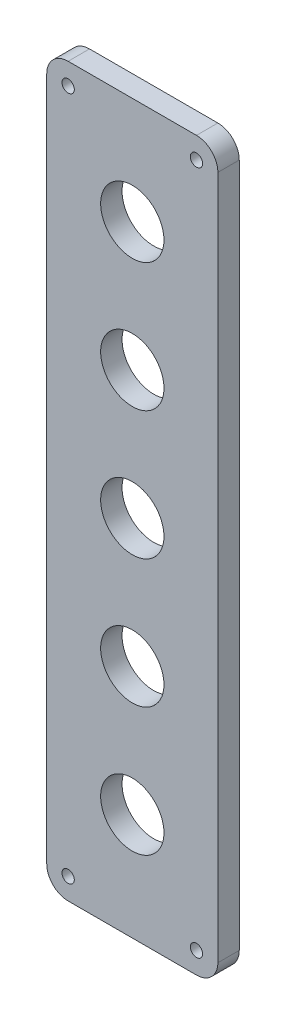
SolidWorks part; units mm, degrees
ref_plane "Front Plane" through (0, 0, 0) normal (0, 0, 1) x (1, 0, 0)
ref_plane "Top Plane" through (0, 0, 0) normal (0, 1, 0) x (1, 0, 0)
ref_plane "Right Plane" through (0, 0, 0) normal (1, 0, 0) x (0, 0, -1)
sketch "Sketch1" plane through (0, 0, 0) normal (0, 0, 1) x (1, 0, 0)
  line L1 (-25.4, -107.95) -> (25.4, -107.95)
  line L2 (-25.4, -107.95) -> (-25.4, 107.95)
  line L3 (-25.4, 107.95) -> (25.4, 107.95)
  line L4 (25.4, -107.95) -> (25.4, 107.95)
  line L5 (-25.4, -107.95) -> (25.4, 107.95) construction
  line L6 (-25.4, 107.95) -> (25.4, -107.95) construction
  point P0 (0, 0)
  dimension "D1" = 50.8
  dimension "D2" = 215.9
extrude "Boss-Extrude1" add sketch "Sketch1" along normal blind 6.35
sketch "Sketch2" plane through (0, 0, 6.35) normal (0, 0, 1) x (1, 0, 0)
  circle A0 centre (0, 0) radius 9.398
  dimension "D1" = 18.796
extrude "Cut-Extrude1" cut sketch "Sketch2" against normal blind 6.35
pattern_linear "LPattern1" count 3 spacing 38.1 along (0, -1, 0) count 3 spacing 38.1 along (0, 1, 0) of "Cut-Extrude1"
hole_wizard "#6 Clearance Hole1" positions "Sketch3" profile "Sketch4" hole size "#6" standard "ANSI Inch" end condition through all
sketch "Sketch3" plane through (0, 0, 6.35) normal (0, 0, 1) x (1, 0, 0)
  line L0 (-25.4, 107.95) -> (25.4, -107.95) construction
  line L3 (-19.05, -101.6) -> (19.05, -101.6) construction
  line L4 (-19.05, -101.6) -> (-19.05, 101.6) construction
  line L5 (-19.05, 101.6) -> (19.05, 101.6) construction
  line L6 (19.05, -101.6) -> (19.05, 101.6) construction
  line L7 (-19.05, -101.6) -> (19.05, 101.6) construction
  line L8 (-19.05, 101.6) -> (19.05, -101.6) construction
  line L9 (25.4, -107.95) -> (25.4, 107.95) construction
  line L10 (25.4, 107.95) -> (-25.4, 107.95) construction
  point P6 (0, 0)
  point P7 (19.05, 101.6)
  point P82 (-19.05, -101.6)
  point P83 (-19.05, 101.6)
  point P84 (19.05, -101.6)
  dimension "D1" = 6.35
  dimension "D2" = 6.35
sketch "Sketch4" plane through (19.05, -101.6, 6.35) normal (1, 0, 0) x (0, -1, 0)
  line L0 (0, 0) -> (0, 6.35)
  line L1 (0, 6.35) -> (1.8288, 6.35)
  line L2 (1.8288, 6.35) -> (1.8288, 0)
  line L5 (1.8288, 0) -> (0, 0)
  line L11 (0, -6.35) -> (0, 107.95) construction
  dimension "Thru Hole Dia." = 3.6576
  dimension "Thru Hole Depth" = 6.35
fillet "Fillet1" radius 6.35 4 edges at (-25.4, -107.95, 3.175) (25.4, -107.95, 3.175) (25.4, 107.95, 3.175) (-25.4, 107.95, 3.175)
